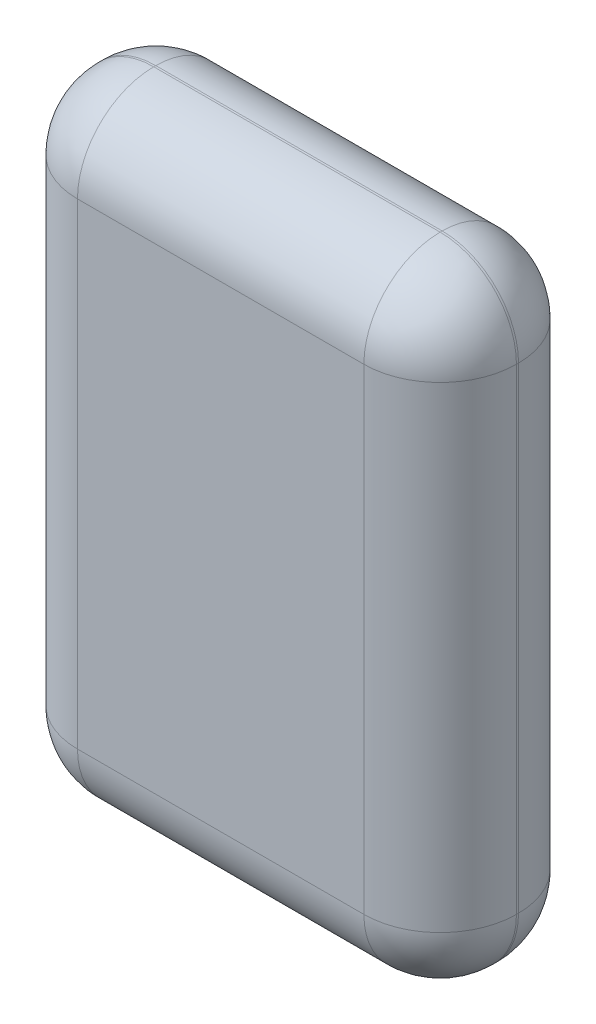
SolidWorks part; units mm, degrees
material "Powerbank SP GP25"
ref_plane "Front Plane" through (0, 0, 0) normal (0, 0, 1) x (1, 0, 0)
ref_plane "Top Plane" through (0, 0, 0) normal (0, 1, 0) x (1, 0, 0)
ref_plane "Right Plane" through (0, 0, 0) normal (1, 0, 0) x (0, 0, -1)
sketch "Sketch1" plane through (0, 0, 0) normal (0, 0, 1) x (1, 0, 0)
  line L1 (-31.65, -45.35) -> (31.65, -45.35)
  line L2 (-31.65, -45.35) -> (-31.65, 45.35)
  line L3 (-31.65, 45.35) -> (31.65, 45.35)
  line L4 (31.65, -45.35) -> (31.65, 45.35)
  line L5 (-31.65, -45.35) -> (31.65, 45.35) construction
  line L6 (-31.65, 45.35) -> (31.65, -45.35) construction
  point P0 (0, 0)
  dimension "D1" = 90.7
  dimension "D2" = 63.3
extrude "Boss-Extrude1" add sketch "Sketch1" along normal mid plane 22.3
fillet "Fillet1" radius 11 12 edges at (-31.65, 0, -11.15) (31.65, 0, -11.15) (-31.65, 0, 11.15) (31.65, 0, 11.15) (-31.65, -45.35, 0) (0, -45.35, 11.15) (31.65, -45.35, 0) (0, -45.35, -11.15) (31.65, 45.35, 0) (0, 45.35, 11.15) (-31.65, 45.35, 0) (0, 45.35, -11.15)
